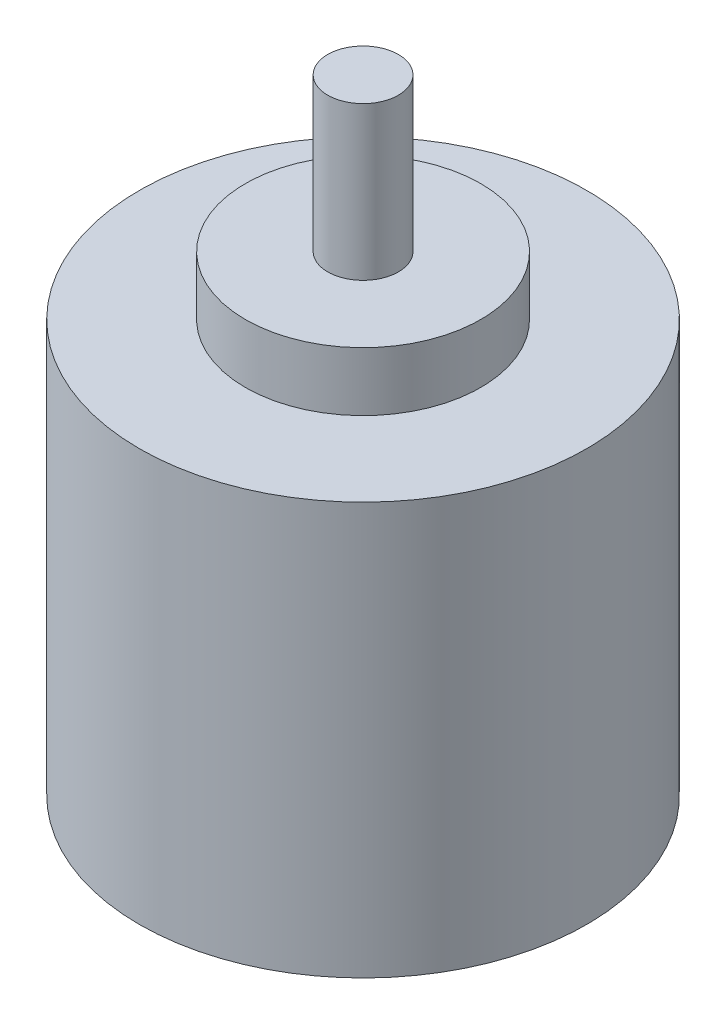
SolidWorks part; units mm, degrees
ref_plane "Front Plane" through (0, 0, 0) normal (0, 0, 1) x (1, 0, 0)
ref_plane "Top Plane" through (0, 0, 0) normal (0, 1, 0) x (1, 0, 0)
ref_plane "Right Plane" through (0, 0, 0) normal (1, 0, 0) x (0, 0, -1)
sketch "Sketch1" plane through (0, 0, 0) normal (0, 1, 0) x (1, 0, 0)
  circle A0 centre (0, 0) radius 19
extrude "Boss-Extrude1" add sketch "Sketch1" along normal blind 35
sketch "Sketch2" plane through (0, 35, 0) normal (0, 1, 0) x (1, 0, 0)
  circle A0 centre (0, 0) radius 10
extrude "Boss-Extrude2" add sketch "Sketch2" along normal blind 5
sketch "Sketch3" plane through (0, 40, 0) normal (0, 1, 0) x (1, 0, 0)
  circle A0 centre (0, 0) radius 3
extrude "Boss-Extrude3" add sketch "Sketch3" along normal blind 13
